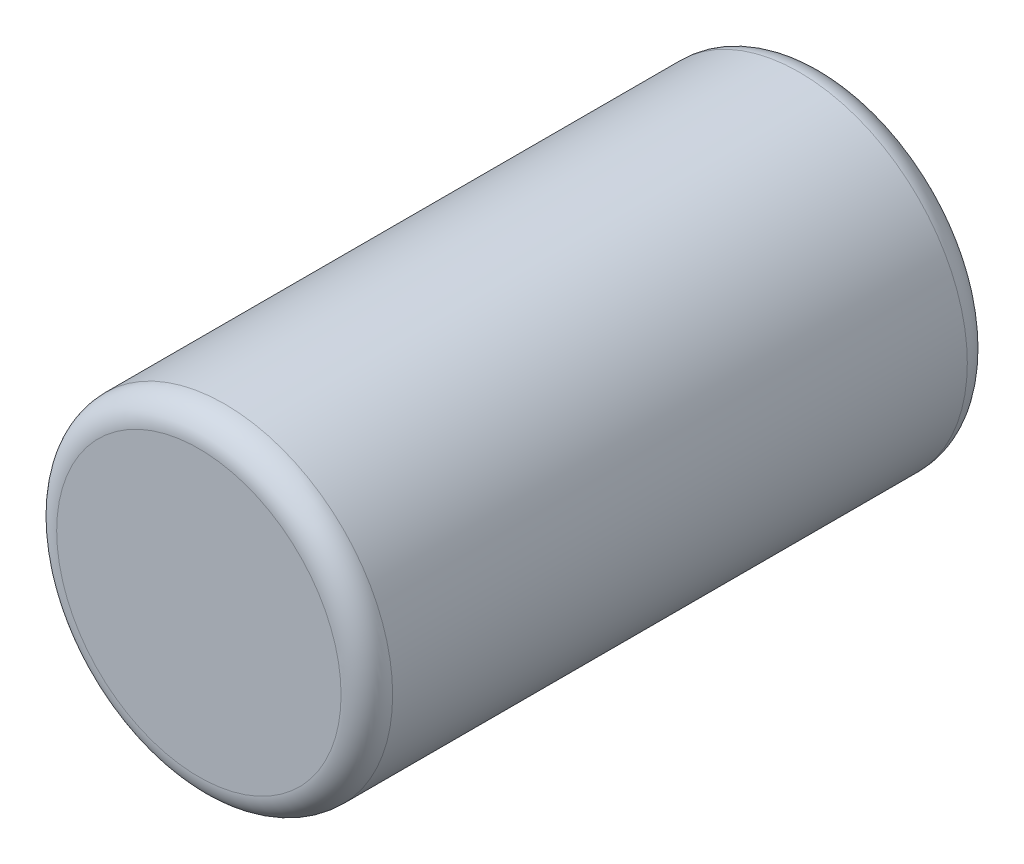
SolidWorks part; units mm, degrees
material "POM Acetal Copolymer"
ref_plane "Front Plane" through (0, 0, 0) normal (0, 0, 1) x (1, 0, 0)
ref_plane "Top Plane" through (0, 0, 0) normal (0, 1, 0) x (1, 0, 0)
ref_plane "Right Plane" through (0, 0, 0) normal (1, 0, 0) x (0, 0, -1)
sketch "Sketch1" plane through (0, 0, 0) normal (1, 0, 0) x (0, 0, -1)
  line L0 (0, 0) -> (42.5, 0)
  line L1 (42.5, 0) -> (42.5, 9.65)
  line L2 (40.75, 11.4) -> (1.75, 11.4)
  line L5 (0, 9.65) -> (0, 0)
  arc A0 (42.5, 9.65) -> (40.75, 11.4) centre (40.75, 9.65) ccw
  arc A2 (0, 9.65) -> (1.75, 11.4) centre (1.75, 9.65) cw
  dimension "D5" = 1.75
  dimension "D4" = 1.75
  dimension "D1" = 42.5
  dimension "D3" = 11.4
revolve "Revolve1" add sketch "Sketch1" angle 360 about L0
